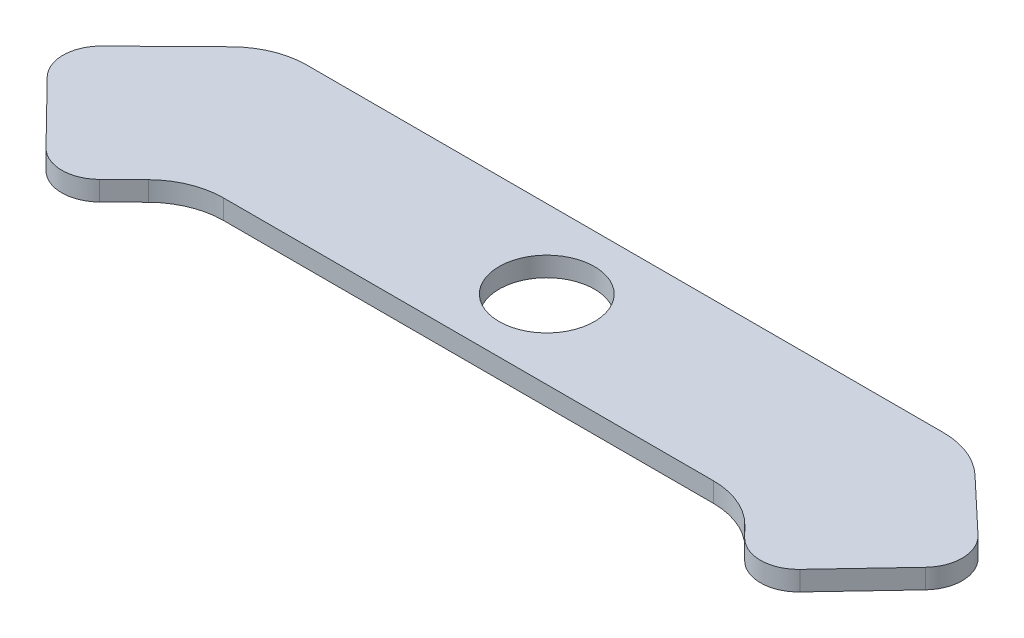
SolidWorks part; units mm, degrees
ref_plane "Front Plane" through (0, 0, 0) normal (0, 0, 1) x (1, 0, 0)
ref_plane "Top Plane" through (0, 0, 0) normal (0, 1, 0) x (1, 0, 0)
ref_plane "Right Plane" through (0, 0, 0) normal (1, 0, 0) x (0, 0, -1)
sketch "Sketch2" plane through (0, 0, 0) normal (0, 1, 0) x (1, 0, 0)
  line L0 (37.8469, 5.8749) -> (43.3416, 0.6877)
  line L1 (32.5, 8) -> (-32.5, 8)
  line L2 (-37.9523, 5.7735) -> (-44.6488, -0.7904)
  line L3 (-44.7039, -6.2978) -> (-38.4828, -12.6446)
  line L4 (-32.9754, -12.6997) -> (-30.4523, -10.2265)
  line L5 (-25, -8) -> (25, -8)
  line L6 (30.5625, -10.3367) -> (31.6649, -11.4614)
  line L7 (37.2781, -11.4087) -> (43.5001, -4.8177)
  line L8 (25, -8) -> (0, -8)
  line L9 (0, 0) -> (0, -8) construction
  line L10 (0, 0) -> (0, 8) construction
  arc A0 (-32.5, 8) -> (-37.9523, 5.7735) centre (-32.5, 0.211) ccw
  arc A1 (32.5, 8) -> (37.8469, 5.8749) centre (32.5, 0.211) cw
  arc A2 (25, -8) -> (30.5625, -10.3367) centre (25, -15.789) cw
  arc A3 (-25, -8) -> (-30.4523, -10.2265) centre (-25, -15.789) ccw
  arc A4 (-44.6488, -0.7904) -> (-44.7039, -6.2978) centre (-41.9226, -3.5717) ccw
  arc A5 (-38.4828, -12.6446) -> (-32.9754, -12.6997) centre (-35.7015, -9.9184) ccw
  arc A6 (43.3416, 0.6877) -> (43.5001, -4.8177) centre (40.6682, -2.1442) cw
  arc A7 (37.2781, -11.4087) -> (31.6649, -11.4614) centre (34.4461, -8.7353) cw
  circle A8 centre (0, 0) radius 4.8681
  point P29 (0, 8)
  dimension "D1" = 8
  dimension "D2" = 8
  dimension "D3" = 65
  dimension "D4" = 50
extrude "Boss-Extrude1" add sketch "Sketch2" along normal blind 2 contours A7 L7 A6 L0 A1 L1 A0 L2 A4 L3 A5 L4 A3 L5 A2 L6 A8
